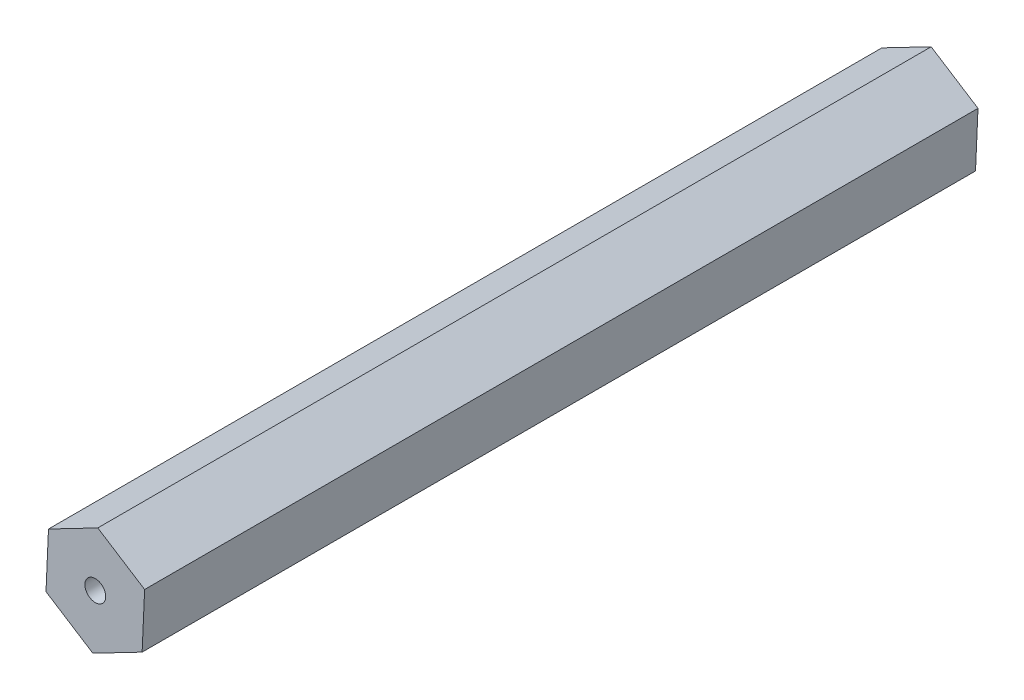
SolidWorks part; units mm, degrees
ref_plane "Front Plane" through (0, 0, 0) normal (0, 0, 1) x (1, 0, 0)
ref_plane "Top Plane" through (0, 0, 0) normal (0, 1, 0) x (1, 0, 0)
ref_plane "Right Plane" through (0, 0, 0) normal (1, 0, 0) x (0, 0, -1)
sketch "Sketch1" plane through (0, 0, 0) normal (0, 0, 1) x (1, 0, 0)
  line L1 (3.3712, -2.1528) -> (3.55, 1.8432)
  line L2 (3.55, 1.8432) -> (0.1788, 3.996)
  line L3 (0.1788, 3.996) -> (-3.3712, 2.1528)
  line L4 (-3.3712, 2.1528) -> (-3.55, -1.8432)
  line L5 (-3.55, -1.8432) -> (-0.1788, -3.996)
  line L6 (-0.1788, -3.996) -> (3.3712, -2.1528)
  circle A0 centre (0, 0) radius 4 construction
  dimension "D1" = 8
extrude "Boss-Extrude1" add sketch "Sketch1" along normal blind 60
sketch "Sketch2" plane through (0, 0, 60) normal (0, 0, 1) x (1, 0, 0)
  circle A0 centre (0, 0) radius 0.75
  dimension "D1" = 1.5
extrude "Cut-Extrude1" cut sketch "Sketch2" against normal blind 5
sketch "Sketch3" plane through (0, 0, 0) normal (0, 0, -1) x (-1, 0, 0)
  circle A0 centre (0, 0) radius 0.75
  dimension "D1" = 1.5
extrude "Cut-Extrude2" cut sketch "Sketch3" against normal blind 5
